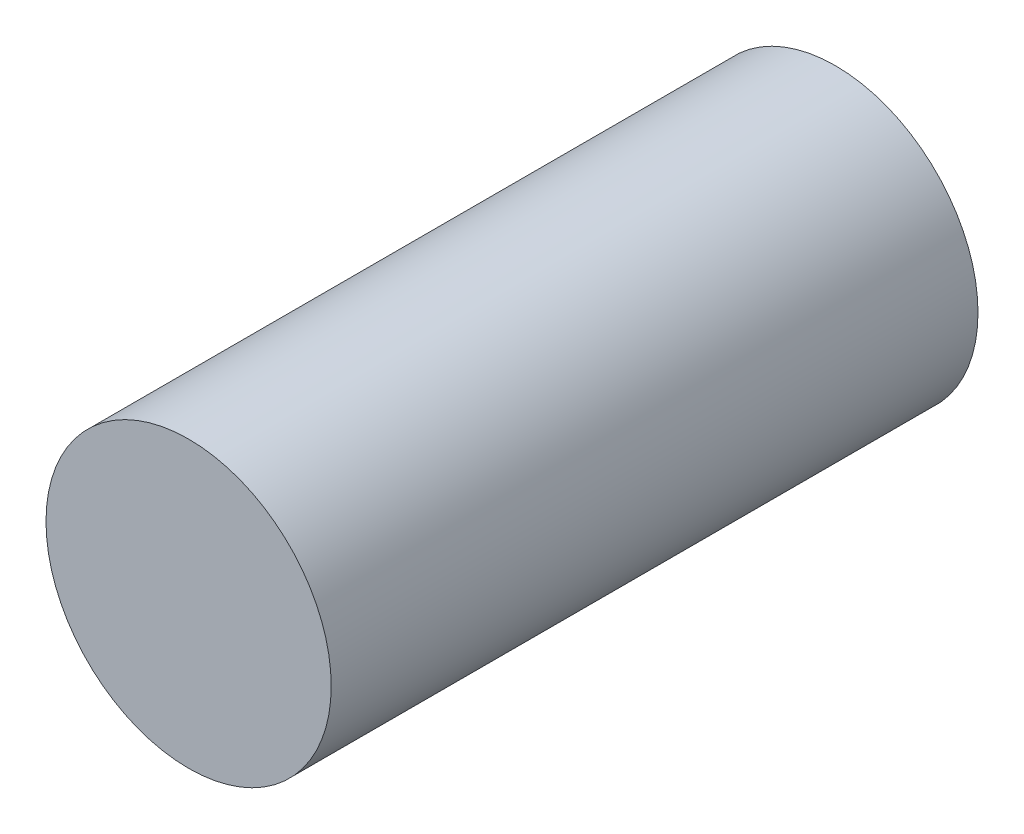
SolidWorks part; units mm, degrees
ref_plane "Front Plane" through (0, 0, 0) normal (0, 0, 1) x (1, 0, 0)
ref_plane "Top Plane" through (0, 0, 0) normal (0, 1, 0) x (1, 0, 0)
ref_plane "Right Plane" through (0, 0, 0) normal (1, 0, 0) x (0, 0, -1)
sketch "Sketch2" plane through (0, 0, 0) normal (0, 0, 1) x (1, 0, 0)
  circle A0 centre (0, 0) radius 27.051
  dimension "D1" = 54.102
extrude "Boss-Extrude1" add sketch "Sketch2" along normal blind 122.682
